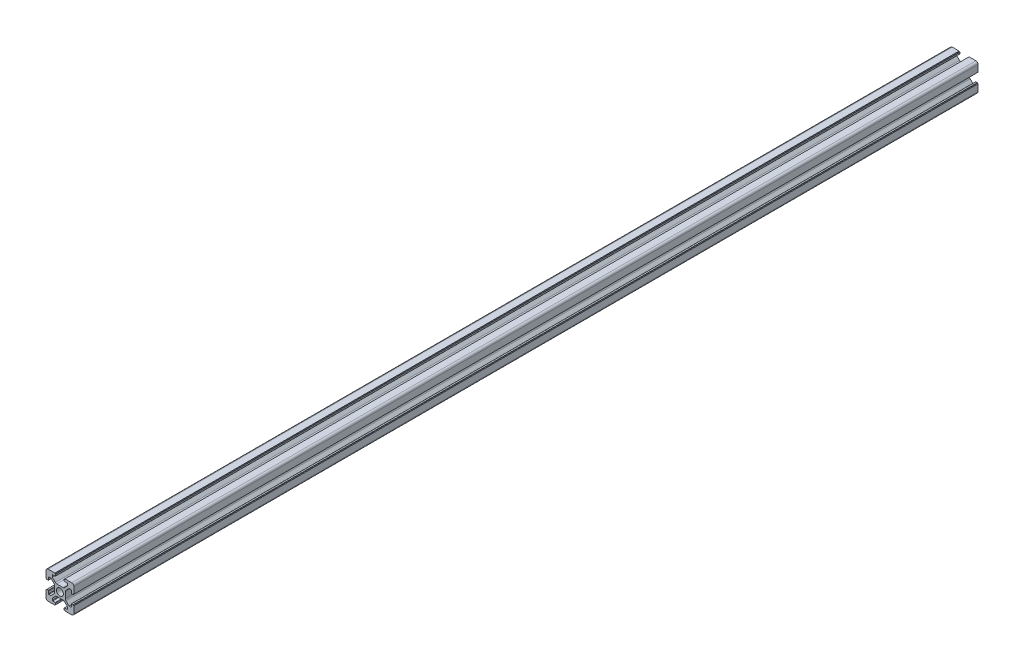
SolidWorks part; units mm, degrees
ref_plane "前视基准面" through (0, 0, 0) normal (0, 0, 1) x (1, 0, 0)
ref_plane "上视基准面" through (0, 0, 0) normal (0, 1, 0) x (1, 0, 0)
ref_plane "右视基准面" through (0, 0, 0) normal (1, 0, 0) x (0, 0, -1)
sketch "草图1" plane through (0, 0, 0) normal (0, 0, 1) x (1, 0, 0)
  line L0 (4.216, 3.2442) -> (6.4367, 5.4649)
  line L1 (6.4367, 5.4649) -> (7.7767, 5.4649)
  line L2 (8.0767, 5.1649) -> (8.0767, 3.3649)
  line L3 (8.3767, 3.0649) -> (9.3767, 3.0649)
  line L4 (9.3767, 3.0649) -> (9.3767, 3.3649)
  line L5 (9.5767, 3.5649) -> (9.8767, 3.5649)
  line L6 (9.8767, 3.5649) -> (9.8767, 8.4649)
  line L7 (8.3767, 9.9649) -> (3.4767, 9.9649)
  line L8 (3.4767, 9.9649) -> (3.4767, 9.6649)
  line L9 (3.2767, 9.4649) -> (2.9767, 9.4649)
  line L10 (2.9767, 9.4649) -> (2.9767, 8.4649)
  line L11 (3.2767, 8.1649) -> (5.0767, 8.1649)
  line L12 (5.3767, 7.8649) -> (5.3767, 6.5249)
  line L13 (5.3767, 6.5249) -> (3.156, 4.3042)
  line L14 (2.0953, 3.8649) -> (-2.342, 3.8649)
  line L15 (-3.4027, 4.3042) -> (-5.6233, 6.5249)
  line L16 (-5.6233, 6.5249) -> (-5.6233, 7.8649)
  line L17 (-5.3233, 8.1649) -> (-3.5233, 8.1649)
  line L18 (-3.2233, 8.4649) -> (-3.2233, 9.4649)
  line L19 (-3.2233, 9.4649) -> (-3.5233, 9.4649)
  line L20 (-3.7233, 9.6649) -> (-3.7233, 9.9649)
  line L21 (-3.7233, 9.9649) -> (-8.6233, 9.9649)
  line L22 (-10.1233, 8.4649) -> (-10.1233, 3.5649)
  line L23 (-10.1233, 3.5649) -> (-9.8233, 3.5649)
  line L24 (-9.6233, 3.3649) -> (-9.6233, 3.0649)
  line L25 (-9.6233, 3.0649) -> (-8.6233, 3.0649)
  line L26 (-8.3233, 3.3649) -> (-8.3233, 5.1649)
  line L27 (-8.0233, 5.4649) -> (-6.6833, 5.4649)
  line L28 (-6.6833, 5.4649) -> (-4.4627, 3.2442)
  line L29 (-4.0233, 2.1836) -> (-4.0233, -2.2538)
  line L30 (-4.4627, -3.3144) -> (-6.6833, -5.5351)
  line L31 (-6.6833, -5.5351) -> (-8.0233, -5.5351)
  line L32 (-8.3233, -5.2351) -> (-8.3233, -3.4351)
  line L33 (-8.6233, -3.1351) -> (-9.6233, -3.1351)
  line L34 (-9.6233, -3.1351) -> (-9.6233, -3.4351)
  line L35 (-9.8233, -3.6351) -> (-10.1233, -3.6351)
  line L36 (-10.1233, -3.6351) -> (-10.1233, -8.5351)
  line L37 (-8.6233, -10.0351) -> (-3.7233, -10.0351)
  line L38 (-3.7233, -10.0351) -> (-3.7233, -9.7351)
  line L39 (-3.5233, -9.5351) -> (-3.2233, -9.5351)
  line L40 (-3.2233, -9.5351) -> (-3.2233, -8.5351)
  line L41 (-3.5233, -8.2351) -> (-5.3233, -8.2351)
  line L42 (-5.6233, -7.9351) -> (-5.6233, -6.5951)
  line L43 (-5.6233, -6.5951) -> (-3.4027, -4.3744)
  line L44 (-2.342, -3.9351) -> (2.0953, -3.9351)
  line L45 (3.156, -4.3744) -> (5.3767, -6.5951)
  line L46 (5.3767, -6.5951) -> (5.3767, -7.9351)
  line L47 (5.0767, -8.2351) -> (3.2767, -8.2351)
  line L48 (2.9767, -8.5351) -> (2.9767, -9.5351)
  line L49 (2.9767, -9.5351) -> (3.2767, -9.5351)
  line L50 (3.4767, -9.7351) -> (3.4767, -10.0351)
  line L51 (3.4767, -10.0351) -> (8.3767, -10.0351)
  line L52 (9.8767, -8.5351) -> (9.8767, -3.6351)
  line L53 (9.8767, -3.6351) -> (9.5767, -3.6351)
  line L54 (9.3767, -3.4351) -> (9.3767, -3.1351)
  line L55 (9.3767, -3.1351) -> (8.3767, -3.1351)
  line L56 (8.0767, -3.4351) -> (8.0767, -5.2351)
  line L57 (7.7767, -5.5351) -> (6.4367, -5.5351)
  line L58 (6.4367, -5.5351) -> (4.216, -3.3144)
  line L59 (3.7767, -2.2538) -> (3.7767, 2.1836)
  circle A0 centre (-0.1233, -0.0351) radius 2.5
  arc A1 (8.0767, 5.1649) -> (7.7767, 5.4649) centre (7.7767, 5.1649) ccw
  arc A2 (8.0767, 3.3649) -> (8.3767, 3.0649) centre (8.3767, 3.3649) ccw
  arc A3 (9.5767, 3.5649) -> (9.3767, 3.3649) centre (9.5767, 3.3649) ccw
  arc A4 (9.8767, 8.4649) -> (8.3767, 9.9649) centre (8.3767, 8.4649) ccw
  arc A5 (3.2767, 9.4649) -> (3.4767, 9.6649) centre (3.2767, 9.6649) ccw
  arc A6 (2.9767, 8.4649) -> (3.2767, 8.1649) centre (3.2767, 8.4649) ccw
  arc A7 (5.3767, 7.8649) -> (5.0767, 8.1649) centre (5.0767, 7.8649) ccw
  arc A8 (2.0953, 3.8649) -> (3.156, 4.3042) centre (2.0953, 5.3649) ccw
  arc A9 (-3.4027, 4.3042) -> (-2.342, 3.8649) centre (-2.342, 5.3649) ccw
  arc A10 (-5.3233, 8.1649) -> (-5.6233, 7.8649) centre (-5.3233, 7.8649) ccw
  arc A11 (-3.5233, 8.1649) -> (-3.2233, 8.4649) centre (-3.5233, 8.4649) ccw
  arc A12 (-3.7233, 9.6649) -> (-3.5233, 9.4649) centre (-3.5233, 9.6649) ccw
  arc A13 (-8.6233, 9.9649) -> (-10.1233, 8.4649) centre (-8.6233, 8.4649) ccw
  arc A14 (-9.6233, 3.3649) -> (-9.8233, 3.5649) centre (-9.8233, 3.3649) ccw
  arc A15 (-8.6233, 3.0649) -> (-8.3233, 3.3649) centre (-8.6233, 3.3649) ccw
  arc A16 (-8.0233, 5.4649) -> (-8.3233, 5.1649) centre (-8.0233, 5.1649) ccw
  arc A17 (-4.0233, 2.1836) -> (-4.4627, 3.2442) centre (-5.5233, 2.1836) ccw
  arc A18 (-4.4627, -3.3144) -> (-4.0233, -2.2538) centre (-5.5233, -2.2538) ccw
  arc A19 (-8.3233, -5.2351) -> (-8.0233, -5.5351) centre (-8.0233, -5.2351) ccw
  arc A20 (-8.3233, -3.4351) -> (-8.6233, -3.1351) centre (-8.6233, -3.4351) ccw
  arc A21 (-9.8233, -3.6351) -> (-9.6233, -3.4351) centre (-9.8233, -3.4351) ccw
  arc A22 (-10.1233, -8.5351) -> (-8.6233, -10.0351) centre (-8.6233, -8.5351) ccw
  arc A23 (-3.5233, -9.5351) -> (-3.7233, -9.7351) centre (-3.5233, -9.7351) ccw
  arc A24 (-3.2233, -8.5351) -> (-3.5233, -8.2351) centre (-3.5233, -8.5351) ccw
  arc A25 (-5.6233, -7.9351) -> (-5.3233, -8.2351) centre (-5.3233, -7.9351) ccw
  arc A26 (-2.342, -3.9351) -> (-3.4027, -4.3744) centre (-2.342, -5.4351) ccw
  arc A27 (3.156, -4.3744) -> (2.0953, -3.9351) centre (2.0953, -5.4351) ccw
  arc A28 (5.0767, -8.2351) -> (5.3767, -7.9351) centre (5.0767, -7.9351) ccw
  arc A29 (3.2767, -8.2351) -> (2.9767, -8.5351) centre (3.2767, -8.5351) ccw
  arc A30 (3.4767, -9.7351) -> (3.2767, -9.5351) centre (3.2767, -9.7351) ccw
  arc A31 (8.3767, -10.0351) -> (9.8767, -8.5351) centre (8.3767, -8.5351) ccw
  arc A32 (9.3767, -3.4351) -> (9.5767, -3.6351) centre (9.5767, -3.4351) ccw
  arc A33 (8.3767, -3.1351) -> (8.0767, -3.4351) centre (8.3767, -3.4351) ccw
  arc A34 (7.7767, -5.5351) -> (8.0767, -5.2351) centre (7.7767, -5.2351) ccw
  arc A35 (3.7767, -2.2538) -> (4.216, -3.3144) centre (5.2767, -2.2538) ccw
  arc A36 (4.216, 3.2442) -> (3.7767, 2.1836) centre (5.2767, 2.1836) ccw
extrude "凸台-拉伸1" add sketch "草图1" along normal blind 650
